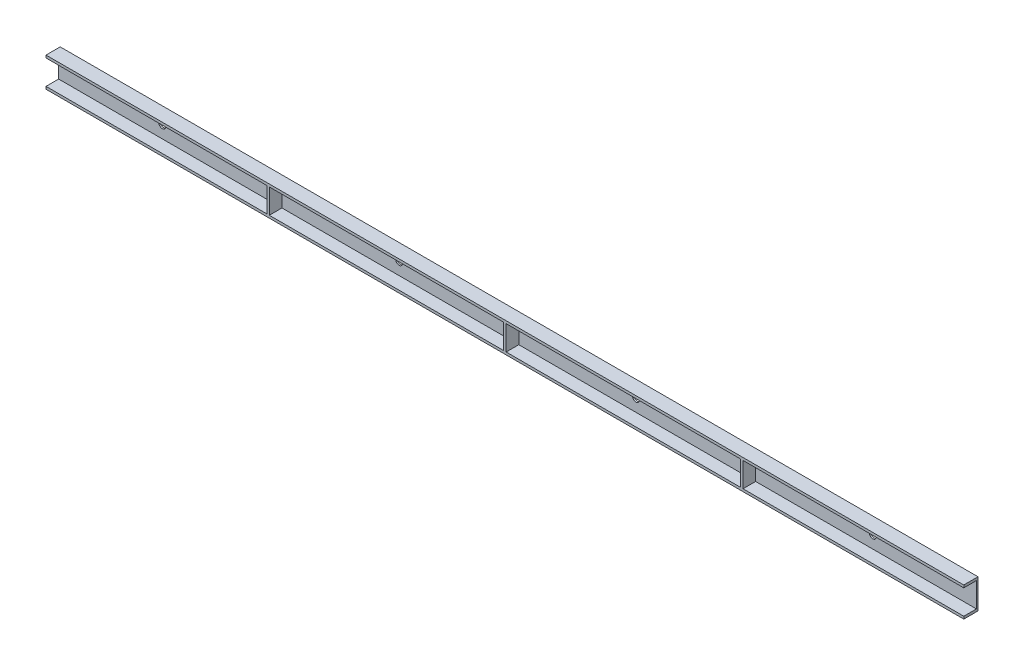
SolidWorks part; units mm, degrees
ref_plane "前视基准面" through (0, 0, 0) normal (0, 0, 1) x (1, 0, 0)
ref_plane "上视基准面" through (0, 0, 0) normal (0, 1, 0) x (1, 0, 0)
ref_plane "右视基准面" through (0, 0, 0) normal (1, 0, 0) x (0, 0, -1)
sketch "草图1" plane through (0, 0, 0) normal (0, 0, 1) x (1, 0, 0)
  line L1 (0, 0) -> (4300, 0)
  line L2 (0, 0) -> (0, 100)
  line L3 (0, 100) -> (4300, 100)
  line L4 (4300, 0) -> (4300, 100)
  dimension "D1" = 4300
  dimension "D2" = 100
extrude "拉伸1" add sketch "草图1" along normal blind 48
sketch "草图2" plane through (0, 0, 48) normal (0, 0, 1) x (1, 0, 0)
  line L0 (0, 100) -> (0, 0) construction
  line L1 (0, 91.5) -> (4300, 91.5)
  line L2 (0, 91.5) -> (0, 8.5)
  line L3 (0, 8.5) -> (4300, 8.5)
  line L4 (4300, 91.5) -> (4300, 8.5)
  line L5 (4300, 100) -> (0, 100) construction
  line L6 (0, 0) -> (4300, 0) construction
  line L7 (4300, 0) -> (4300, 100) construction
  dimension "D1" = 8.5
  dimension "D2" = 8.5
extrude "拉伸2" cut sketch "草图2" against normal blind 42.7
sketch "草图3" plane through (0, 0, 5.3) normal (0, 0, 1) x (1, 0, 0)
  line L0 (4300, 91.5) -> (0, 91.5) construction
  line L1 (545.75, 91.5) -> (554.25, 91.5)
  line L2 (545.75, 91.5) -> (545.75, 8.5)
  line L3 (545.75, 8.5) -> (554.25, 8.5)
  line L4 (554.25, 91.5) -> (554.25, 8.5)
  line L5 (0, 8.5) -> (4300, 8.5) construction
  line L6 (550, 91.5) -> (550, 8.5) construction
  line L7 (0, 91.5) -> (0, 8.5) construction
  dimension "D1" = 8.5
  dimension "D2" = 550
extrude "拉伸3" add sketch "草图3" along normal blind 42.7
pattern_linear "阵列(线性)1" count 5 spacing 800 along (1, 0, 0) of "拉伸3"
sketch "草图4" plane through (0, 0, 0) normal (0, 0, -1) x (-1, 0, 0)
  line L0 (-4300, 50) -> (0, 50) construction
  line L1 (-4300, 0) -> (-4300, 100) construction
  line L2 (0, 100) -> (0, 0) construction
  circle A0 centre (-4150, 50) radius 11.5
  dimension "D1" = 23
  dimension "D2" = 150
extrude "拉伸4" cut sketch "草图4" against normal through all
pattern_linear "阵列(线性)2" count 6 spacing 800 along (-1, 0, 0) of "拉伸4"
sketch "草图5" plane through (0, 100, 0) normal (0, 1, 0) x (-1, 0, 0)
  line L0 (-4300, 48) -> (0, 48) construction
  line L1 (0, 0) -> (-600, 0)
  line L2 (0, 0) -> (0, 48)
  line L3 (0, 48) -> (-600, 48)
  line L4 (-600, 0) -> (-600, 48)
  line L5 (-4300, 0) -> (0, 0) construction
  line L6 (-4300, 48) -> (-3700, 48)
  line L7 (-4300, 48) -> (-4300, 0)
  line L8 (-4300, 0) -> (-3700, 0)
  line L9 (-3700, 48) -> (-3700, 0)
  dimension "D1" = 600
  dimension "D2" = 600
extrude "切除-拉伸1" cut sketch "草图5" against normal blind 100
